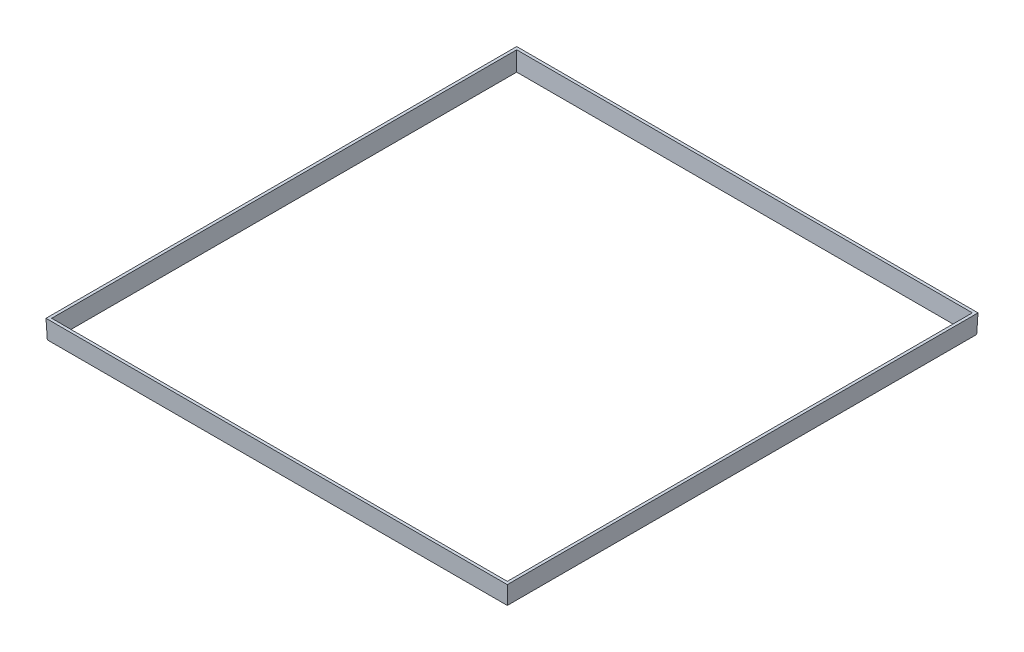
SolidWorks part; units mm, degrees
material "Polyurethane Foam Flexible"
ref_plane "Front Plane" through (0, 0, 0) normal (0, 0, 1) x (1, 0, 0)
ref_plane "Top Plane" through (0, 0, 0) normal (0, 1, 0) x (1, 0, 0)
ref_plane "Right Plane" through (0, 0, 0) normal (1, 0, 0) x (0, 0, -1)
sketch "Sketch2" plane through (0, 0, 0) normal (0, 1, 0) x (1, 0, 0)
  line L13 (-123, -125.5) -> (123, -125.5)
  line L14 (-123, -125.5) -> (-123, 125.5)
  line L15 (-123, 125.5) -> (123, 125.5)
  line L16 (123, -125.5) -> (123, 125.5)
  line L17 (-123, -125.5) -> (123, 125.5) construction
  line L18 (-123, 125.5) -> (123, -125.5) construction
  point P0 (0, 0)
  dimension "D1" = 246
  dimension "D2" = 251
extrude "Boss-Extrude1" add sketch "Sketch2" against normal blind 10 draft 2
sketch "Sketch5" plane through (0, 0, 0) normal (0, 1, 0) x (1, 0, 0)
  line L14 (121.5, -124) -> (121.5, 124)
  line L15 (-121.5, -124) -> (121.5, -124)
  line L16 (-121.5, 124) -> (-121.5, -124)
  line L17 (121.5, 124) -> (-121.5, 124)
  line L18 (121.5, -124) -> (121.5, 124)
  line L19 (-121.5, -124) -> (121.5, -124)
  line L20 (-121.5, 124) -> (-121.5, -124)
  line L21 (121.5, 124) -> (-121.5, 124)
  dimension "D1" = 1.5
extrude "Cut-Extrude1" cut sketch "Sketch5" against normal through all draft 2
sketch "Sketch9" plane through (0, -4.3772, 125.3471) normal (0, -0.0349, 0.9994) x (1, 0, 0)
  line L0 (-123, 4.3799) -> (-122.6512, -5.614) construction
  line L1 (-122.6508, -5.6262) -> (-123, 4.3799) construction
  line L2 (-122.6512, -5.614) -> (-122.6508, -5.6262)
  line L3 (-122.6508, -5.6262) -> (122.6508, -5.6262)
  line L4 (122.6508, -5.6262) -> (122.6512, -5.614)
  line L5 (122.6508, -5.6262) -> (123, 4.3799) construction
  line L6 (-122.6512, -5.614) -> (122.6512, -5.614)
  dimension "D1" = 10
extrude "Cut-Extrude2" cut sketch "Sketch9" along direction (0, 0, 1) on the side against the normal through all
